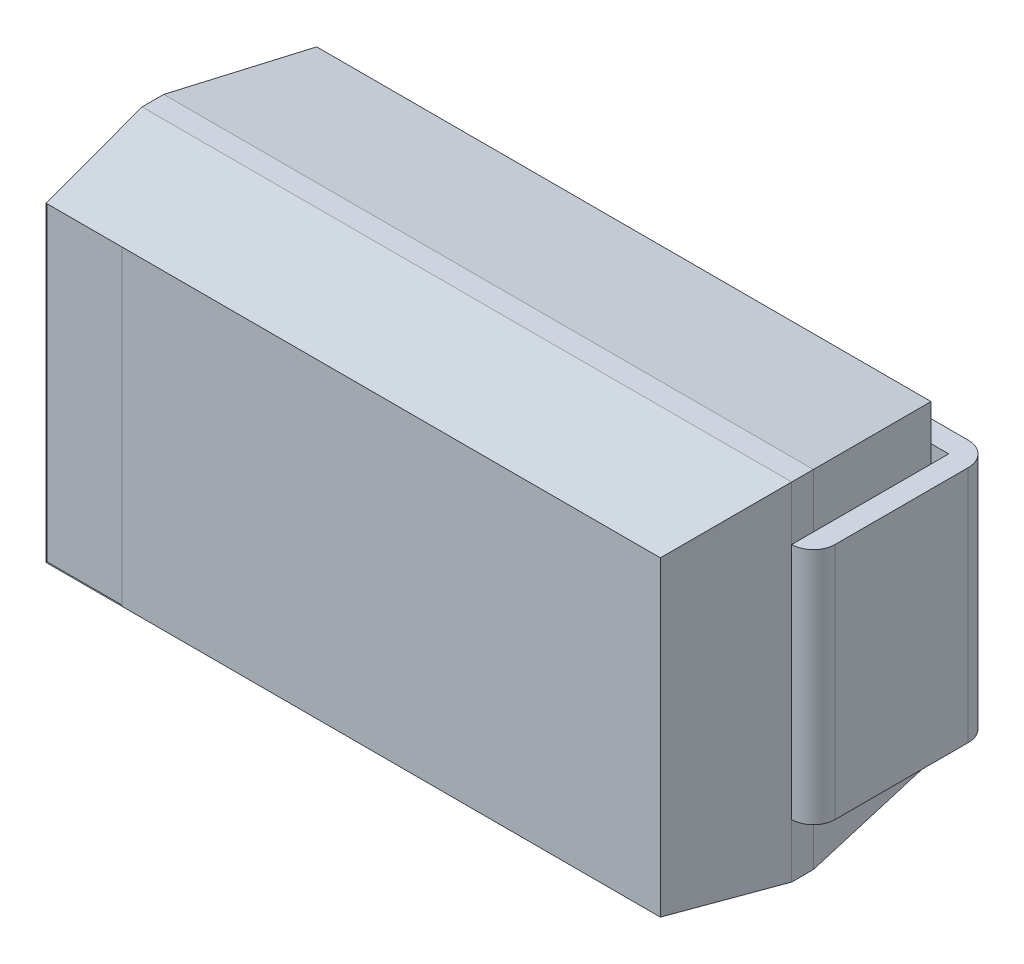
SolidWorks part; units mm, degrees
other "Детальный элемент1"
ref_plane "Спереди" through (0, 0, 0) normal (0, 0, 1) x (1, 0, 0)
ref_plane "Сверху" through (0, 0, 0) normal (0, 1, 0) x (1, 0, 0)
ref_plane "Справа" through (0, 0, 0) normal (1, 0, 0) x (0, 0, -1)
ref_plane "Плоскость1" through (0, 0, 0.2) normal (0, 0, 1) x (1, 0, 0)
sketch "Эскиз1" plane through (0, 0, 0.2) normal (0, 0, 1) x (1, 0, 0)
  line L1 (-3, 1.6) -> (3, 1.6)
  line L2 (-3, 1.6) -> (-3, -1.6)
  line L3 (-3, -1.6) -> (3, -1.6)
  line L4 (3, 1.6) -> (3, -1.6)
  line L5 (-3, 1.6) -> (3, -1.6) construction
  line L6 (-3, -1.6) -> (3, 1.6) construction
  point P0 (0, 0)
  dimension "D1" = 6
  dimension "D2" = 3.2
extrude "Бобышка-Вытянуть1" add sketch "Эскиз1" along normal blind 2.5
chamfer "Фаска1" distance 1.05 distance2 0.163 4 edges at (0, 1.6, 2.7) (3, 0, 2.7) (0, -1.6, 2.7) (-3, 0, 2.7)
chamfer "Фаска2" distance 0.163 distance2 1.25 4 edges at (3, 0, 0.2) (0, 1.6, 0.2) (0, -1.6, 0.2) (-3, 0, 0.2)
sketch "Эскиз2" plane through (0, 0, 0) normal (0, 1, 0) x (1, 0, 0)
  line L0 (-3, -0.2) -> (-3, -1.45)
  line L1 (-1.9, 0) -> (-2.98, 0)
  line L2 (-1.9, 0) -> (-1.9, -0.2)
  line L3 (-1.9, -0.2) -> (-3, -0.2)
  line L4 (-3, -1.45) -> (-3, -1.65)
  line L5 (-3.2, -1.45) -> (-3.2, -0.22)
  arc A2 (-3, -1.65) -> (-3.2, -1.45) centre (-3, -1.45) cw
  arc A3 (-2.98, 0) -> (-3.2, -0.22) centre (-2.98, -0.22) ccw
  dimension "D3" = 0.22
  dimension "D1" = 0.2
  dimension "D2" = 0.2
  dimension "D4" = 1.3
extrude "Бобышка-Вытянуть2" add sketch "Эскиз2" along normal blind 1.1 and the other way blind 1.1 separate body
mirror "Зеркальное отражение1" about plane through (0, 0, 0) normal (1, 0, 0) of bodies 108
sketch "Эскиз3" plane through (0, 0, 2.7) normal (0, 0, 1) x (1, 0, 0)
  line L0 (2.837, 1.437) -> (-2.837, 1.437) construction
  line L1 (-2.837, -1.437) -> (-2.137, -1.437)
  line L2 (-2.837, -1.437) -> (-2.837, 1.437)
  line L3 (-2.837, 1.437) -> (-2.137, 1.437)
  line L4 (-2.137, -1.437) -> (-2.137, 1.437)
  dimension "D1" = 0.7
extrude "Вырез-Вытянуть1" cut sketch "Эскиз3" against normal blind 0.01
